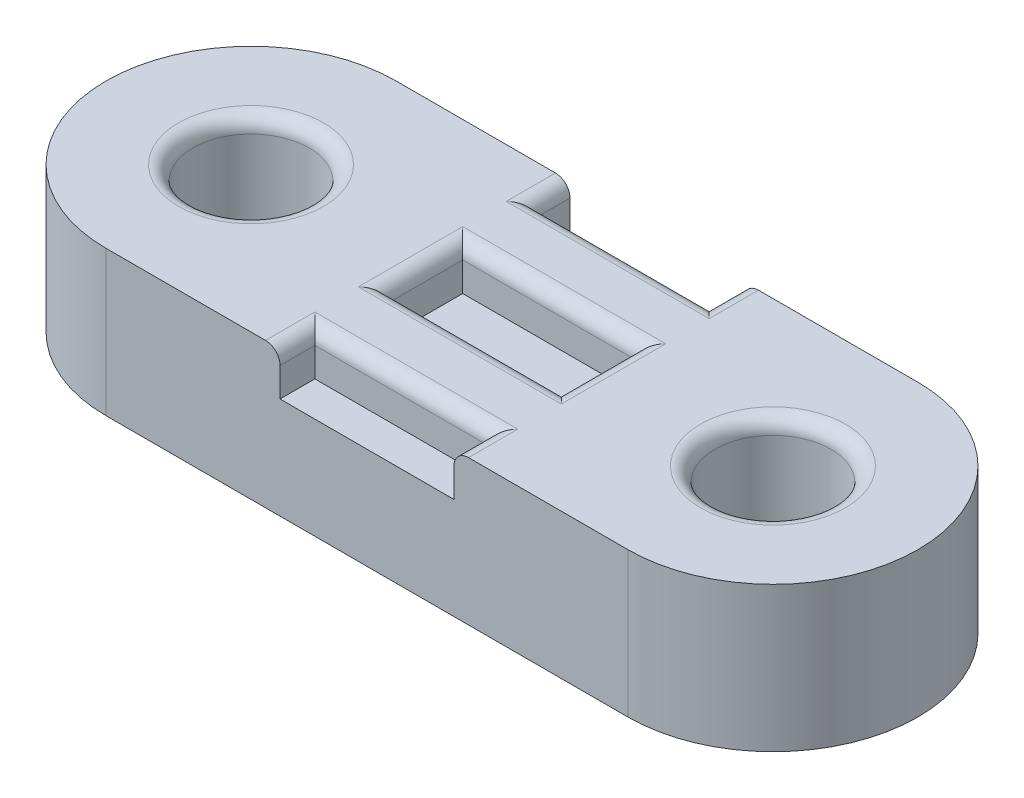
SolidWorks part; units mm, degrees
ref_plane "Front Plane" through (0, 0, 0) normal (0, 0, 1) x (1, 0, 0)
ref_plane "Top Plane" through (0, 0, 0) normal (0, 1, 0) x (1, 0, 0)
ref_plane "Right Plane" through (0, 0, 0) normal (1, 0, 0) x (0, 0, -1)
sketch "Belt Clamp" plane through (0, 0, 0) normal (0, 1, 0) x (1, 0, 0)
  line L1 (-18, 10) -> (0, 10)
  line L3 (-18, 0) -> (0, 0)
  arc A0 (-18, 10) -> (-18, 0) centre (-18, 5) ccw
  arc A1 (0, 0) -> (0, 10) centre (0, 5) ccw
  dimension "D1" = 18
  dimension "D2" = 10
extrude "Boss-Extrude1" add sketch "Belt Clamp" along normal blind 5
sketch "Screw Holes" plane through (0, 0, 0) normal (0, -1, 0) x (1, 0, 0)
  circle A0 centre (-18, -5) radius 2
  circle A1 centre (0, -5) radius 2
  dimension "D1" = 4
extrude "Cut-Extrude1" cut sketch "Screw Holes" against normal up to surface (5 mm away) up to face at (-9, 5, -5)
fillet "Fillet2" radius 0.5 4 edges at (0, 5, -3) (-18, 5, -3) (0, 0, -7) (-18, 0, -7)
sketch "Belt cut outs" plane through (0, 5, 0) normal (0, 1, 0) x (1, 0, 0)
  line L0 (-9, 0) -> (-9, 10) construction
  line L3 (-18, 0) -> (0, 0) construction
  line L4 (5, 5) -> (-23, 5) construction
  line L5 (0, 10) -> (-18, 10) construction
  line L7 (-6, 0) -> (-12, 0)
  line L8 (-6, 0) -> (-6, 1.2)
  line L9 (-6, 1.2) -> (-12, 1.2)
  line L10 (-12, 0) -> (-12, 1.2)
  line L11 (-6, 0) -> (-12, 1.2) construction
  line L12 (-6, 1.2) -> (-12, 0) construction
  line L13 (-6, 3.7) -> (-12, 3.7)
  line L14 (-6, 3.7) -> (-6, 6.3)
  line L15 (-6, 6.3) -> (-12, 6.3)
  line L16 (-12, 3.7) -> (-12, 6.3)
  line L17 (-6, 3.7) -> (-12, 6.3) construction
  line L18 (-6, 6.3) -> (-12, 3.7) construction
  line L19 (-6, 8.8) -> (-12, 8.8)
  line L20 (-6, 8.8) -> (-6, 10)
  line L21 (-6, 10) -> (-12, 10)
  line L22 (-12, 8.8) -> (-12, 10)
  line L23 (-6, 8.8) -> (-12, 10) construction
  line L24 (-6, 10) -> (-12, 8.8) construction
  arc A0 (0, 0) -> (0, 10) centre (0, 5) ccw construction
  arc A1 (-18, 10) -> (-18, 0) centre (-18, 5) ccw construction
  point P6 (-9, 0.6)
  point P19 (-9, 9.4)
  point P22 (-9, 5)
  dimension "D1" = 6
  dimension "D2" = 2.6
  dimension "D3" = 1.2
extrude "Cut-Extrude2" cut sketch "Belt cut outs" against normal blind 1.5
fillet "Fillet3" radius 0.5 10 edges at (-6, 5, -0.6) (-9, 5, -1.2) (-12, 5, -0.6) (-12, 5, -5) (-9, 5, -3.7) (-6, 5, -5) (-9, 5, -6.3) (-12, 5, -9.4) (-6, 5, -9.4) (-9, 5, -8.8)
